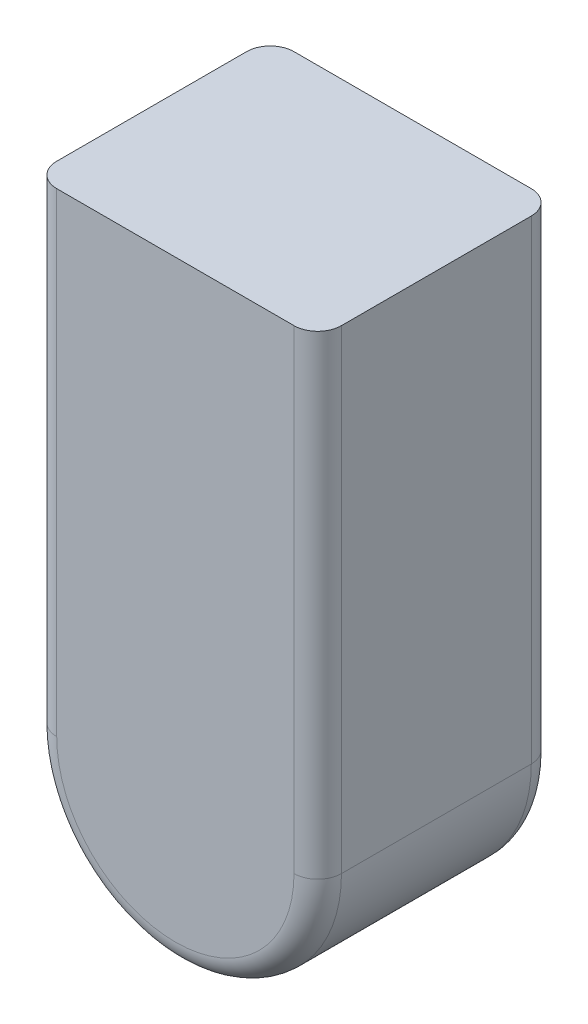
SolidWorks part; units mm, degrees
ref_plane "Front Plane" through (0, 0, 0) normal (0, 0, 1) x (1, 0, 0)
ref_plane "Top Plane" through (0, 0, 0) normal (0, 1, 0) x (1, 0, 0)
ref_plane "Right Plane" through (0, 0, 0) normal (1, 0, 0) x (0, 0, -1)
sketch "Sketch2" plane through (0, 0, 0) normal (0, 0, 1) x (1, 0, 0)
  line L0 (-6, 0) -> (-6, 20)
  line L1 (-6, 20) -> (6, 20)
  line L2 (6, 20) -> (6, 0)
  arc A0 (-6, 0) -> (6, 0) centre (0, 0) ccw
  dimension "D1" = 12
  dimension "D2" = 20
extrude "Boss-Extrude1" add sketch "Sketch2" along normal mid plane 10
fillet "Fillet1" radius 1 6 edges at (0, -6, 5) (0, -6, -5) (-6, 10, 5) (-6, 10, -5) (6, 10, -5) (6, 10, 5)
